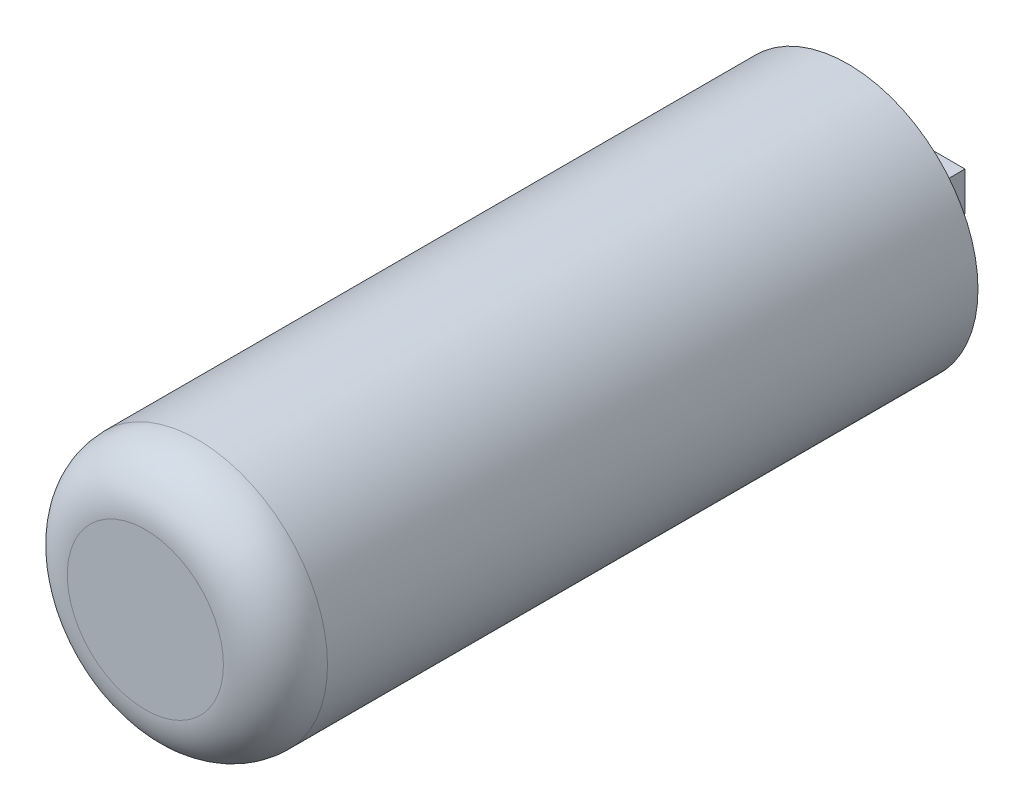
SolidWorks part; units mm, degrees
ref_plane "Front Plane" through (0, 0, 0) normal (0, 0, 1) x (1, 0, 0)
ref_plane "Top Plane" through (0, 0, 0) normal (0, 1, 0) x (1, 0, 0)
ref_plane "Right Plane" through (0, 0, 0) normal (1, 0, 0) x (0, 0, -1)
sketch "Sketch1" plane through (0, 0, 0) normal (0, 0, 1) x (1, 0, 0)
  circle A0 centre (0, 0) radius 5
  dimension "D1" = 10
extrude "Boss-Extrude1" add sketch "Sketch1" along normal blind 27
fillet "Fillet1" radius 2 1 edges at (5, 0, 27)
sketch "Sketch2" plane through (0, 0, 0) normal (0, 0, -1) x (-1, 0, 0)
  line L1 (-1.5, 0.75) -> (1.5, 0.75)
  line L2 (-1.5, 0.75) -> (-1.5, -0.75)
  line L3 (-1.5, -0.75) -> (1.5, -0.75)
  line L4 (1.5, 0.75) -> (1.5, -0.75)
  line L5 (-1.5, 0.75) -> (1.5, -0.75) construction
  line L6 (-1.5, -0.75) -> (1.5, 0.75) construction
  point P0 (0, 0)
  dimension "D1" = 3
  dimension "D2" = 1.5
extrude "Boss-Extrude2" add sketch "Sketch2" along normal blind 3
sketch "Sketch3" plane through (0, 0.75, 0) normal (0, 1, 0) x (1, 0, 0)
  line L0 (1.5, 1.5) -> (-1.5, 1.5) construction
  line L1 (1.5, 3) -> (1.5, 0) construction
  line L2 (-1.5, 3) -> (-1.5, 0) construction
  circle A0 centre (0, 1.5) radius 0.75
  point P8 (0, 0)
  point P9 (0, 1.5)
  dimension "D1" = 1.5
extrude "Cut-Extrude1" cut sketch "Sketch3" against normal blind 5
